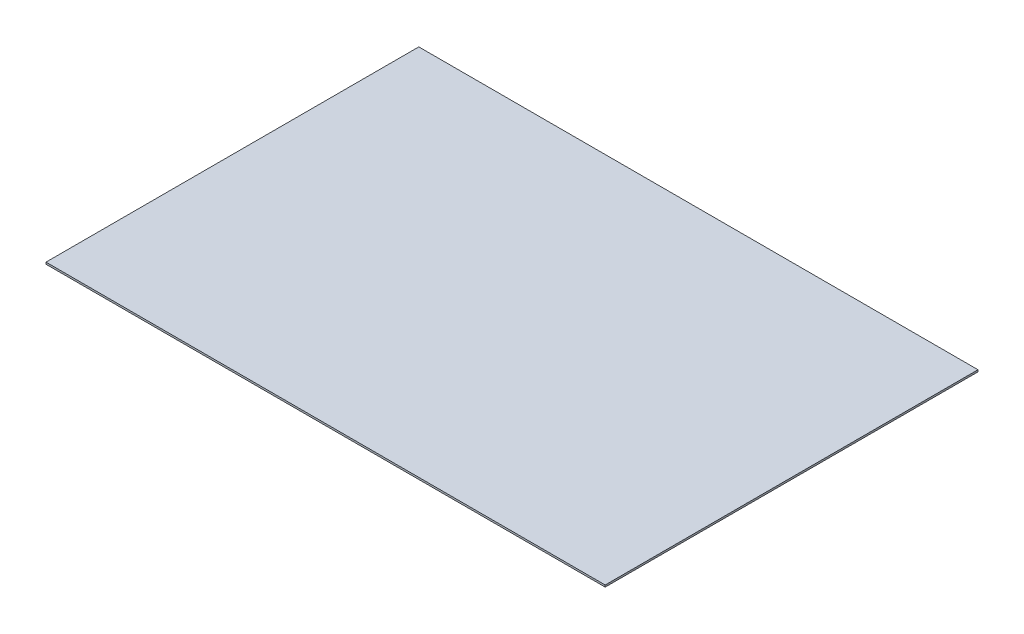
SolidWorks part; units mm, degrees
ref_plane "Front Plane" through (0, 0, 0) normal (0, 0, 1) x (1, 0, 0)
ref_plane "Top Plane" through (0, 0, 0) normal (0, 1, 0) x (1, 0, 0)
ref_plane "Right Plane" through (0, 0, 0) normal (1, 0, 0) x (0, 0, -1)
sketch "Sketch1" plane through (0, 0, 0) normal (0, 1, 0) x (1, 0, 0)
  line L1 (0, 0) -> (600, 0)
  line L2 (0, 0) -> (0, 400)
  line L3 (0, 400) -> (600, 400)
  line L4 (600, 0) -> (600, 400)
  dimension "D1" = 600
  dimension "D2" = 400
extrude "Boss-Extrude1" add sketch "Sketch1" along normal blind 2 contours L1 L4 L3 L2
